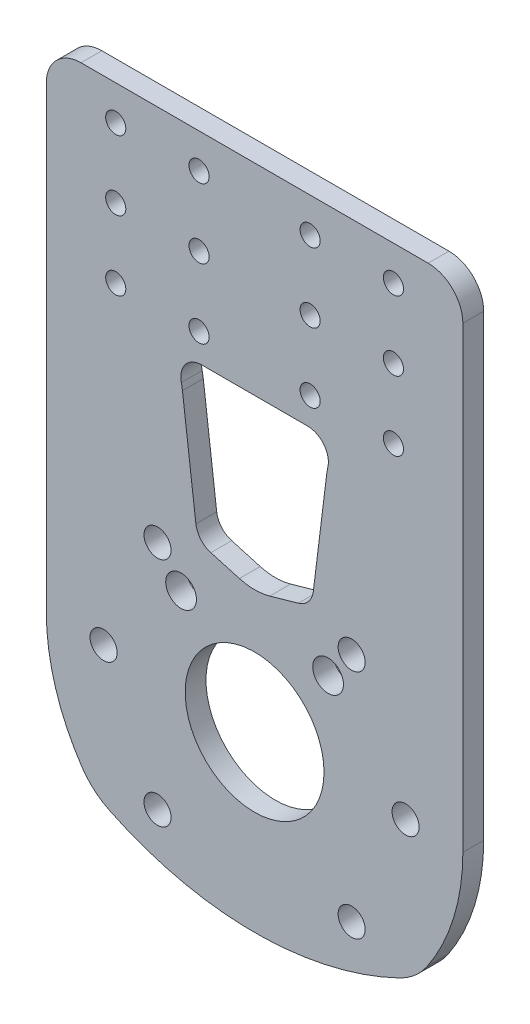
SolidWorks part; units mm, degrees
material "Thornel Mat VMA"
ref_plane "前视基准面" through (0, 0, 0) normal (0, 0, 1) x (1, 0, 0)
ref_plane "上视基准面" through (0, 0, 0) normal (0, 1, 0) x (1, 0, 0)
ref_plane "右视基准面" through (0, 0, 0) normal (1, 0, 0) x (0, 0, -1)
sketch "草图1" plane through (0, 0, 0) normal (0, 0, 1) x (1, 0, 0)
  line L0 (0, -299.5376) -> (0, 14677.34) construction
  line L1 (-30, 31) -> (30, 31)
  line L2 (-30, 31) -> (-30, -40)
  line L3 (-30, -40) -> (30, -40) construction
  line L4 (30, 31) -> (30, -40)
  line L5 (-8, 31) -> (-8, -40) construction
  line L6 (-20, 31) -> (-20, -40) construction
  circle A0 centre (-20, 26) radius 1.45
  circle A1 centre (-20, 16) radius 1.45
  circle A2 centre (-20, 6) radius 1.45
  circle A3 centre (-8, 26) radius 1.45
  circle A4 centre (-8, 16) radius 1.45
  circle A5 centre (-8, 6) radius 1.45
  circle A6 centre (8, 6) radius 1.45
  circle A7 centre (8, 16) radius 1.45
  circle A8 centre (8, 26) radius 1.45
  circle A9 centre (20, 6) radius 1.45
  circle A10 centre (20, 16) radius 1.45
  circle A11 centre (20, 26) radius 1.45
  arc A12 (-30, -40) -> (30, -40) centre (0, -40) ccw
  point P4 (0, 31)
  dimension "D3" = 2.9
  dimension "D1" = 8
  dimension "D2" = 12
  dimension "D4" = 5
  dimension "D5" = 10
  dimension "D6" = 10
  dimension "D7" = 6
  dimension "D8" = 60
  dimension "D9" = 40
extrude "凸台-拉伸1" add sketch "草图1" along normal blind 3
sketch "草图3" plane through (0, 0, 3) normal (0, 0, 1) x (1, 0, 0)
  line L0 (-21.75, -40) -> (21.75, -40) construction
  line L1 (-13.9806, -23.3385) -> (0, -40) construction
  line L2 (0, -40) -> (13.9806, -56.6615) construction
  line L3 (-13.9806, -56.6615) -> (0, -40) construction
  line L4 (0, -40) -> (13.9806, -23.3385) construction
  circle A0 centre (0, -40) radius 21.75 construction
  circle A1 centre (-21.75, -40) radius 1.95
  circle A2 centre (-13.9806, -23.3385) radius 1.95
  circle A3 centre (-13.9806, -56.6615) radius 1.95
  circle A4 centre (21.75, -40) radius 1.95
  circle A5 centre (13.9806, -23.3385) radius 1.95
  circle A6 centre (13.9806, -56.6615) radius 1.95
  dimension "D1" = 43.5
  dimension "D4" = 3.9
  dimension "D2" = 50
  dimension "D3" = 50
extrude "切除-拉伸2" cut sketch "草图3" against normal through all
fillet "圆角1" radius 5 2 edges at (30, 31, 1.5) (-30, 31, 1.5)
sketch "草图4" plane through (0, 0, 3) normal (0, 0, 1) x (1, 0, 0)
  circle A0 centre (0, -40) radius 10
  dimension "D1" = 20
extrude "切除-拉伸3" cut sketch "草图4" against normal through all
sketch "草图5" plane through (0, 0, 3) normal (0, 0, 1) x (1, 0, 0)
  line L0 (0, -40) -> (0, 0) construction
  line L1 (0, -22.5553) -> (-8.212, -20.2183)
  line L2 (-8.212, -20.2183) -> (-10.3898, -2.5978)
  line L3 (-12.385, 2) -> (12.385, 2)
  line L4 (8.212, -20.2183) -> (10.3898, -2.5978)
  line L5 (0, -22.5553) -> (8.212, -20.2183)
  arc A0 (-10.3898, -2.5978) -> (-12.385, 2) centre (-19.1924, -3.6857) ccw
  circle A1 centre (-8, 6) radius 1.45 construction
  arc A2 (10.3898, -2.5978) -> (12.385, 2) centre (19.1924, -3.6857) cw
  arc A3 (-23.18, -59.0444) -> (23.18, -59.0444) centre (0, -16.8895) ccw
  arc A4 (-30, -40) -> (30, -40) centre (0, -40) ccw construction
  circle A6 centre (13.9806, -56.6615) radius 1.95 construction
  circle A7 centre (-10.5873, -27.6567) radius 2.2132
  circle A8 centre (10.5873, -27.6567) radius 2.2132
  arc A9 (-23.18, -59.0444) -> (23.18, -59.0444) centre (0, -40) ccw
  point P21 (0, 2)
  point P33 (0, 0)
  dimension "D2" = 4
  dimension "D1" = 4
extrude "切除-拉伸4" cut sketch "草图5" against normal through all
fillet "圆角2" radius 10 2 edges at (-23.18, -59.0444, 1.5) (23.18, -59.0444, 1.5)
fillet "圆角3" radius 3 4 edges at (-8.212, -20.2183, 1.5) (12.385, 2, 1.5) (8.212, -20.2183, 1.5) (-12.385, 2, 1.5)
fillet "圆角4" radius 8 1 edges at (0, -22.5553, 1.5)
